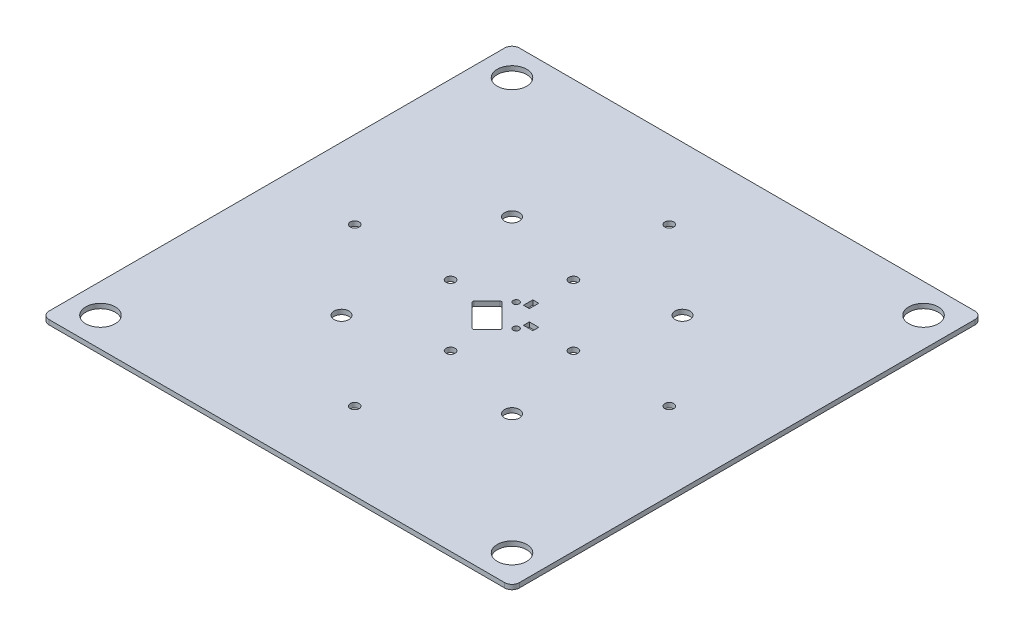
SolidWorks part; units mm, degrees
ref_plane "Front Plane" through (0, 0, 0) normal (0, 0, 1) x (1, 0, 0)
ref_plane "Top Plane" through (0, 0, 0) normal (0, 1, 0) x (1, 0, 0)
ref_plane "Right Plane" through (0, 0, 0) normal (1, 0, 0) x (0, 0, -1)
sketch "Sketch1" plane through (0, 0, 0) normal (0, 1, 0) x (1, 0, 0)
  line L0 (402.2343, 42.2615) -> (557.2343, 42.2615)
  line L1 (559.7343, 39.7615) -> (559.7343, -115.2385)
  line L2 (557.2343, -117.7385) -> (402.2343, -117.7385)
  line L3 (399.7343, -115.2385) -> (399.7343, 39.7615)
  line L33 (481.8556, -43.2539) -> (474.2188, -35.6172)
  line L34 (473.5117, -35.6172) -> (469.1277, -40.0012)
  line L35 (469.1277, -40.7084) -> (476.7644, -48.3451)
  line L36 (477.4715, -48.3451) -> (481.8556, -43.961)
  line L38 (484.6343, -37.7385) -> (484.6343, -36.7385)
  line L39 (484.6343, -36.7385) -> (487.8343, -36.7385)
  line L40 (487.8343, -36.7385) -> (487.8343, -38.7385)
  line L41 (487.8343, -38.7385) -> (484.6343, -38.7385)
  line L42 (484.6343, -38.7385) -> (484.6343, -37.7385)
  line L43 (479.7343, -32.8385) -> (478.7343, -32.8385)
  line L44 (478.7343, -32.8385) -> (478.7343, -29.6385)
  line L45 (478.7343, -29.6385) -> (480.7343, -29.6385)
  line L46 (480.7343, -29.6385) -> (480.7343, -32.8385)
  line L47 (480.7343, -32.8385) -> (479.7343, -32.8385)
  arc A0 (559.7343, 39.7615) -> (557.2343, 42.2615) centre (557.2343, 39.7615) ccw
  arc A1 (557.2343, -117.7385) -> (559.7343, -115.2385) centre (557.2343, -115.2385) ccw
  arc A2 (399.7343, -115.2385) -> (402.2343, -117.7385) centre (402.2343, -115.2385) ccw
  arc A3 (402.2343, 42.2615) -> (399.7343, 39.7615) centre (402.2343, 39.7615) ccw
  circle A4 centre (549.7343, 32.2615) radius 3.05
  circle A5 centre (549.7343, 32.2615) radius 5
  circle A6 centre (409.7343, 32.2615) radius 3.05
  circle A7 centre (409.7343, 32.2615) radius 5
  circle A8 centre (549.7343, -107.7385) radius 3.05
  circle A9 centre (549.7343, -107.7385) radius 5
  circle A10 centre (409.7343, -107.7385) radius 3.05
  circle A11 centre (409.7343, -107.7385) radius 5
  circle A16 centre (500.6343, -37.7385) radius 1.525
  circle A19 centre (458.8343, -37.7385) radius 1.525
  circle A22 centre (479.7343, -16.8385) radius 1.525
  circle A25 centre (479.7343, -58.6385) radius 1.525
  circle A37 centre (476.5523, -33.1423) radius 1.025
  circle A38 centre (484.3305, -40.9205) radius 1.025
  arc A39 (474.2188, -35.6172) -> (473.5117, -35.6172) centre (473.8653, -35.9707) ccw
  arc A40 (469.1277, -40.0012) -> (469.1277, -40.7084) centre (469.4812, -40.3548) ccw
  arc A41 (476.7644, -48.3451) -> (477.4715, -48.3451) centre (477.118, -47.9916) ccw
  arc A42 (481.8556, -43.961) -> (481.8556, -43.2539) centre (481.502, -43.6075) ccw
  circle A43 centre (426.2343, -37.7385) radius 1.525
  circle A44 centre (533.2343, -37.7385) radius 1.525
  circle A45 centre (479.7343, 15.7615) radius 1.525
  circle A46 centre (479.7343, -91.2385) radius 1.525
  circle A55 centre (508.7256, -8.7471) radius 2.525
  circle A56 centre (450.7429, -8.7471) radius 2.525
  circle A57 centre (508.7256, -66.7299) radius 2.525
  circle A58 centre (450.7429, -66.7299) radius 2.525
extrude "Boss-Extrude1" add sketch "Sketch1" along normal blind 1.6 contours L0 A3 L3 A2 L2 A1 L1 A0 A58 A57 A56 A55 A46 A45 A44 A43 A42 L36 A41 L35 A40 L34 A39 L33 A38 A37 A25 A22 A19 A16 A11 A9 A7
